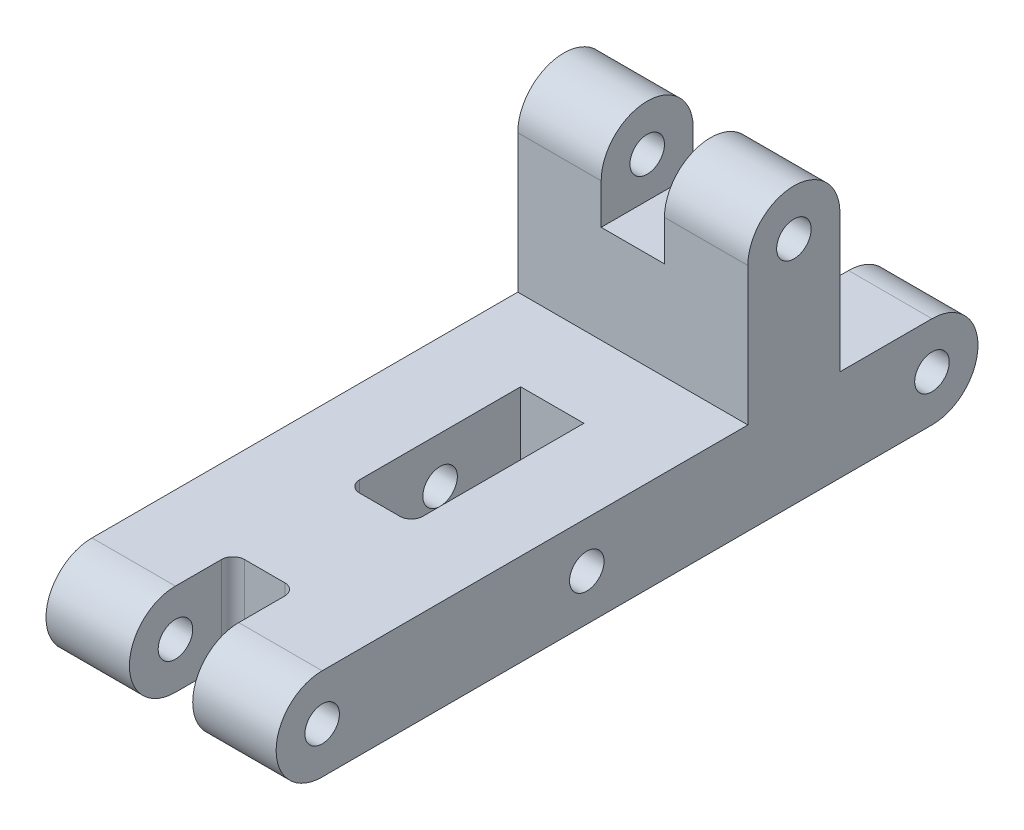
SolidWorks part; units mm, degrees
ref_plane "Alzado" through (0, 0, 0) normal (0, 0, 1) x (1, 0, 0)
ref_plane "Planta" through (0, 0, 0) normal (0, 1, 0) x (1, 0, 0)
ref_plane "Vista lateral" through (0, 0, 0) normal (1, 0, 0) x (0, 0, -1)
sketch "Croquis1" plane through (0, 0, 0) normal (1, 0, 0) x (0, 0, -1)
  line L0 (-15, 0) -> (15, 0) construction
  line L1 (-15, 4) -> (-1, 4)
  line L2 (-15, -4) -> (15, -4)
  line L3 (7, 4) -> (15, 4)
  line L5 (-1, 4) -> (-1, 16)
  line L6 (-1, 16) -> (7, 16) construction
  line L7 (7, 4) -> (7, 16)
  line L8 (-15, 4) -> (-38, 4)
  line L9 (-15, -4) -> (-38, -4)
  line L10 (-38, 4) -> (-38, -4) construction
  arc A0 (-15, 4) -> (-15, -4) centre (-15, 0) ccw construction
  arc A1 (15, -4) -> (15, 4) centre (15, 0) ccw
  circle A2 centre (15, 0) radius 1.5
  arc A3 (7, 16) -> (-1, 16) centre (3, 16) ccw
  circle A4 centre (3, 16) radius 1.5
  circle A5 centre (-15, 0) radius 1.5
  arc A6 (-38, 4) -> (-38, -4) centre (-38, 0) ccw
  circle A7 centre (-38, 0) radius 1.5
  point P3 (0, 0)
  dimension "D2" = 4
  dimension "D3" = 3
  dimension "D4" = 4
  dimension "D7" = 23
  dimension "D1" = 30
  dimension "D5" = 8
  dimension "D6" = 12
extrude "Saliente-Extruir1" add sketch "Croquis1" along normal mid plane 20
sketch "Croquis2" plane through (0, 0, 0) normal (1, 0, 0) x (0, 0, -1)
  line L0 (-1, 16) -> (-1, 4) construction
  line L1 (-1, 12.5) -> (7, 12.5)
  line L2 (-1, 12.5) -> (-1, 20)
  line L3 (-1, 20) -> (7, 20)
  line L4 (7, 12.5) -> (7, 20)
  line L5 (7, 4) -> (7, 16) construction
  line L6 (-1, 4) -> (-38, 4) construction
  line L7 (-8, 4) -> (-23, 4)
  line L8 (-8, 4) -> (-8, -4)
  line L9 (-8, -4) -> (-23, -4)
  line L10 (-23, 4) -> (-23, -4)
  line L11 (-38, -4) -> (15, -4) construction
  line L12 (15, 4) -> (7, 4) construction
  line L13 (10, 4) -> (19, 4)
  line L14 (10, 4) -> (10, -4)
  line L15 (10, -4) -> (19, -4)
  line L16 (19, 4) -> (19, -4)
  line L17 (-1, 4) -> (-38, 4) construction
  line L18 (-33, 4) -> (-42, 4)
  line L19 (-33, 4) -> (-33, -4)
  line L20 (-33, -4) -> (-42, -4)
  line L21 (-42, 4) -> (-42, -4)
  line L22 (-38, -4) -> (15, -4) construction
  arc A0 (7, 16) -> (-1, 16) centre (3, 16) ccw construction
  arc A2 (15, -4) -> (15, 4) centre (15, 0) ccw construction
  circle A4 centre (-15, 0) radius 1.5 construction
  arc A5 (-38, 4) -> (-38, -4) centre (-38, 0) ccw construction
  dimension "D5" = 9
  dimension "D1" = 7.5
  dimension "D2" = 8
  dimension "D3" = 9
  dimension "D4" = 8
extrude "Cortar-Extruir1" cut sketch "Croquis2" against normal mid plane 5.5
fillet "Redondeo1" radius 1 6 edges at (2.75, 0, 23) (-2.75, 0, 23) (2.75, 0, 33) (-2.75, 0, 33) (2.75, 0, -10) (-2.75, 0, -10)
